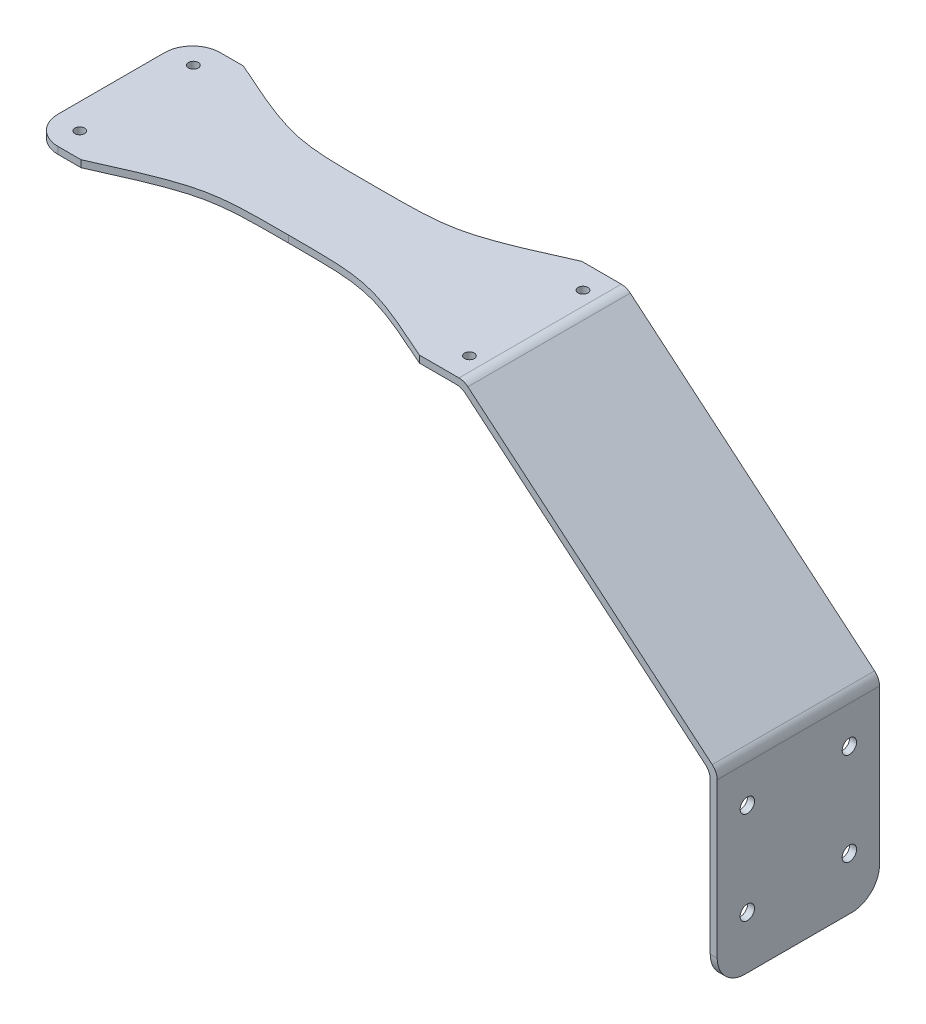
SolidWorks part; units mm, degrees
material "6061 合金"
ref_plane "前视基准面" through (0, 0, 0) normal (0, 0, 1) x (1, 0, 0)
ref_plane "上视基准面" through (0, 0, 0) normal (0, 1, 0) x (1, 0, 0)
ref_plane "右视基准面" through (0, 0, 0) normal (1, 0, 0) x (0, 0, -1)
sketch "草图2" plane through (0, 0, 0) normal (0, 0, 1) x (1, 0, 0)
  line L0 (63.674, 0.4776) -> (63.674, -39.5224)
  line L1 (63.674, 0.4776) -> (10.0509, 45.4727)
  line L2 (10.0509, 45.4727) -> (-82.9491, 45.4727)
  line L3 (-82.9491, 45.4727) -> (-82.9491, 46.9727)
  line L4 (-82.9491, 46.9727) -> (10.5968, 46.9727)
  line L5 (63.674, -39.5224) -> (65.174, -39.5224)
  line L6 (65.174, -39.5224) -> (65.174, 1.1771)
  line L7 (10.5968, 46.9727) -> (65.174, 1.1771)
  dimension "D1" = 40
  dimension "D2" = 93
  dimension "D3" = 1.5
  dimension "D4" = 70
  dimension "D5" = 1.5
  dimension "D6" = 1.5
extrude "凸台-拉伸1" add sketch "草图2" along normal blind 35
fillet "圆角1" radius 3 4 edges at (63.674, 0.4776, 17.5) (65.174, 1.1771, 17.5) (10.5968, 46.9727, 17.5) (10.0509, 45.4727, 17.5)
sketch "草图3" plane through (0, 46.9727, 0) normal (0, 1, 0) x (1, 0, 0)
  line L0 (9.5049, -17.5) -> (-99.2101, -17.5) construction
  line L1 (9.5049, -35) -> (9.5049, 0) construction
  circle A0 centre (6.5049, -5.25) radius 1
  circle A1 centre (-77.4951, -5.25) radius 1
  circle A2 centre (6.5049, -29.75) radius 1
  circle A3 centre (-77.4951, -29.75) radius 1
  dimension "D1" = 12.25
  dimension "D2" = 84
  dimension "D3" = 3
  dimension "D4" = 2
  dimension "D5" = 2
hole_wizard "Ø2.1 (2.1) 直径孔1" positions "3D草图1" profile "草图4" hole size "Ø2.1" standard "GB" end condition up to next
sketch3d "3D草图1"
  point P0 (-77.4951, 46.9727, 5.25)
  point P3 (-77.4951, 46.9727, 29.75)
  point P6 (6.5049, 46.9727, 5.25)
  point P9 (6.5049, 46.9727, 29.75)
sketch "草图4" plane through (-77.4951, 46.9727, 5.25) normal (1, 0, 0) x (0, 0, 1)
  line L0 (0, 0) -> (0, 1.5)
  line L1 (0, 1.5) -> (1.05, 1.5)
  line L2 (1.05, 1.5) -> (1.05, 0)
  line L5 (1.05, 0) -> (0, 0)
  line L11 (0, -6.35) -> (0, 107.95) construction
  dimension "通孔孔直径" = 2.1
  dimension "通孔孔深度" = 1.5
sketch "草图5" plane through (0, 46.9727, 0) normal (0, 1, 0) x (1, 0, 0)
  line L0 (9.5049, -17.5) -> (-97.0428, -17.5) construction
  line L1 (9.5049, -35) -> (9.5049, 0) construction
  line L3 (-77.4951, 2.5024) -> (-77.4951, 12.8452)
  line L4 (-35.4951, -29.75) -> (-35.4951, 10.7767)
  line L5 (-77.4951, 2.5024) -> (-53.5699, -8.3857) construction
  line L7 (-53.5699, -8.3857) -> (-53.5143, -8.3) construction
  line L8 (-53.5143, -8.3) -> (-35.4951, -8.3) construction
  line L9 (6.5049, 2.5024) -> (-17.4202, -8.3857) construction
  line L10 (-17.4202, -8.3857) -> (-17.4759, -8.3) construction
  line L11 (-17.4759, -8.3) -> (-35.4951, -8.3) construction
  line L12 (-77.4951, -37.5024) -> (-53.5699, -26.6143) construction
  line L13 (-53.5699, -26.6143) -> (-53.5143, -26.7) construction
  line L14 (-53.5143, -26.7) -> (-35.4951, -26.7) construction
  line L15 (6.5049, -37.5024) -> (-17.4202, -26.6143) construction
  line L16 (-17.4202, -26.6143) -> (-17.4759, -26.7) construction
  line L17 (-17.4759, -26.7) -> (-35.4951, -26.7) construction
  line L18 (-77.4951, 12.8452) -> (6.5049, 12.8452)
  line L19 (6.5049, 12.8452) -> (6.5049, 2.5024)
  line L20 (-77.4951, -37.5024) -> (-77.4951, -45.4191)
  line L21 (-77.4951, -45.4191) -> (6.5049, -45.4191)
  line L22 (6.5049, -45.4191) -> (6.5049, -37.5024)
  spline S0 degree 3 poles (-77.4951, 2.5024) (-53.5699, -8.3857) (-53.5143, -8.3) (-35.4951, -8.3) knots 0 0 0 0 1 1 1 1
  spline S1 degree 3 poles (6.5049, 2.5024) (-17.4202, -8.3857) (-17.4759, -8.3) (-35.4951, -8.3) knots 0 0 0 0 1 1 1 1
  spline S2 degree 3 poles (-77.4951, -37.5024) (-53.5699, -26.6143) (-53.5143, -26.7) (-35.4951, -26.7) knots 0 0 0 0 1 1 1 1
  spline S3 degree 3 poles (6.5049, -37.5024) (-17.4202, -26.6143) (-17.4759, -26.7) (-35.4951, -26.7) knots 0 0 0 0 1 1 1 1
extrude "切除-拉伸1" cut sketch "草图5" against normal blind 40
sketch "草图6" plane through (65.174, 0, 0) normal (1, 0, 0) x (0, 0, -1)
  line L0 (-17.5, -39.5224) -> (-17.5, 7.6644) construction
  line L1 (-35, -39.5224) -> (0, -39.5224) construction
  line L2 (0, -0.2219) -> (-35, -0.2219) construction
  circle A0 centre (-28.5, -8.2219) radius 1.55
  circle A1 centre (-28.5, -28.2219) radius 1.55
  circle A2 centre (-6.5, -28.2219) radius 1.55
  circle A3 centre (-6.5, -8.2219) radius 1.55
  dimension "D2" = 3.1
  dimension "D3" = 20
  dimension "D4" = 3.1
  dimension "D1" = 8
  dimension "D5" = 22
hole_wizard "Ø3.1 (3.1) 直径孔1" positions "3D草图2" profile "草图7" hole size "Ø3.1" standard "GB" end condition up to next
sketch3d "3D草图2"
  point P0 (65.174, -8.2219, 28.5)
  point P3 (65.174, -8.2219, 6.5)
  point P6 (65.174, -28.2219, 6.5)
  point P9 (65.174, -28.2219, 28.5)
sketch "草图7" plane through (65.174, -8.2219, 28.5) normal (0, 1, 0) x (0, 0, -1)
  line L0 (0, 0) -> (0, 1.5)
  line L1 (0, 1.5) -> (1.55, 1.5)
  line L2 (1.55, 1.5) -> (1.55, 0)
  line L5 (1.55, 0) -> (0, 0)
  line L11 (0, -6.35) -> (0, 107.95) construction
  dimension "通孔孔直径" = 3.1
  dimension "通孔孔深度" = 1.5
fillet "圆角2" radius 6 4 edges at (-82.9491, 46.2227, 35) (-82.9491, 46.2227, 0) (64.424, -39.5224, 35) (64.424, -39.5224, 0)
